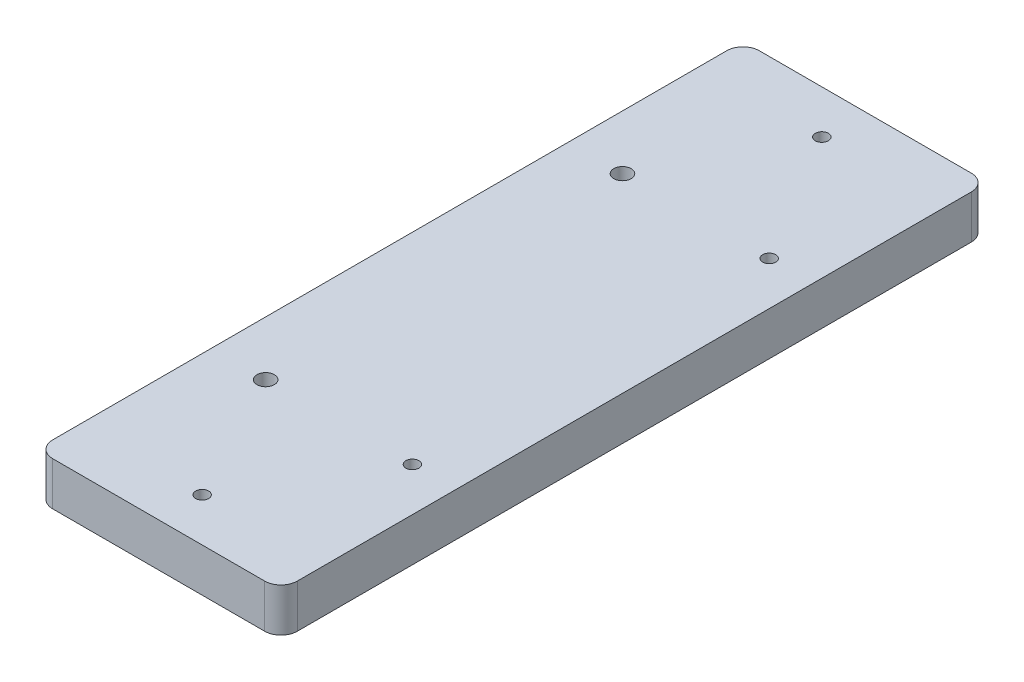
SolidWorks part; units mm, degrees
ref_plane "Front Plane" through (0, 0, 0) normal (0, 0, 1) x (1, 0, 0)
ref_plane "Top Plane" through (0, 0, 0) normal (0, 1, 0) x (1, 0, 0)
ref_plane "Right Plane" through (0, 0, 0) normal (1, 0, 0) x (0, 0, -1)
sketch "Sketch1" plane through (0, 0, 0) normal (0, 1, 0) x (1, 0, 0)
  line L0 (0, 0) -> (0, 130)
  line L1 (0, 130) -> (45, 130)
  line L2 (45, 130) -> (45, 0)
  line L3 (45, 0) -> (0, 0)
  circle A0 centre (10, 97.825) radius 1.6
  circle A1 centre (10, 32.175) radius 1.6
  circle A2 centre (37, 97.825) radius 1.2
  circle A3 centre (37, 32.175) radius 1.2
  circle A4 centre (22.5, 8) radius 1.2
  circle A5 centre (22.5, 122) radius 1.2
  dimension "D3" = 10
  dimension "D1" = 8
  dimension "D2" = 8
extrude "Boss-Extrude1" add sketch "Sketch1" along normal blind 8
fillet "Fillet1" radius 3 4 edges at (0, 4, -130) (45, 4, -130) (45, 4, 0) (0, 4, 0)
sketch "Sketch2" plane through (0, 8, 0) normal (0, 1, 0) x (1, 0, 0)
